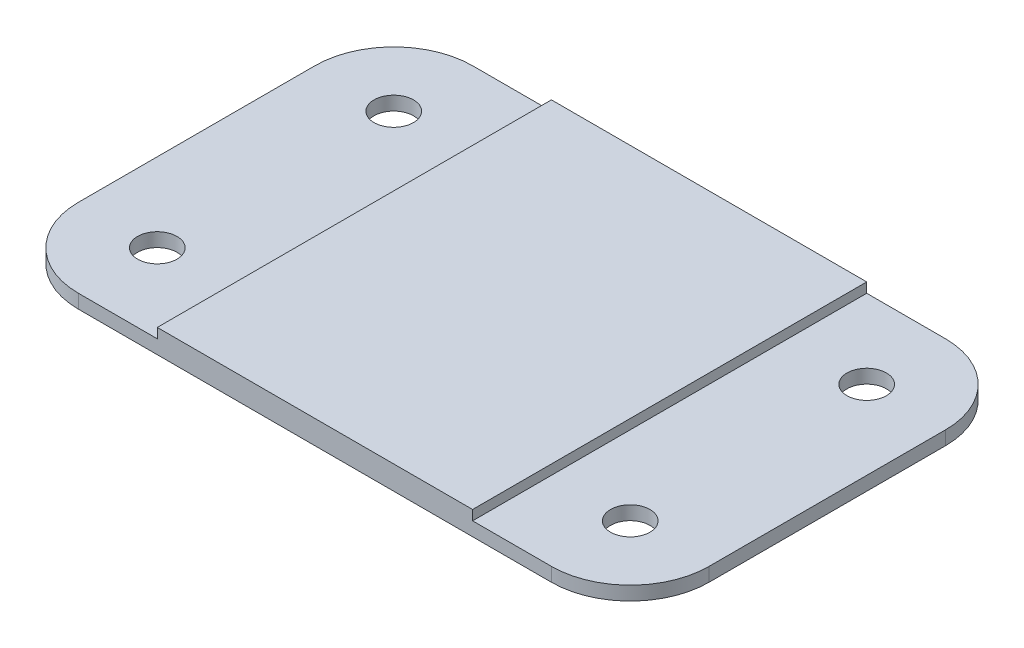
SolidWorks part; units mm, degrees
ref_plane "Front Plane" through (0, 0, 0) normal (0, 0, 1) x (1, 0, 0)
ref_plane "Top Plane" through (0, 0, 0) normal (0, 1, 0) x (1, 0, 0)
ref_plane "Right Plane" through (0, 0, 0) normal (1, 0, 0) x (0, 0, -1)
sketch "Sketch1" plane through (0, 0, 0) normal (0, 1, 0) x (1, 0, 0)
  line L1 (-76.2, 63.5) -> (76.2, 63.5)
  line L2 (-101.6, 38.1) -> (-101.6, -38.1)
  line L3 (-76.2, -63.5) -> (76.2, -63.5)
  line L4 (101.6, 38.1) -> (101.6, -38.1)
  line L5 (-101.6, 63.5) -> (101.6, -63.5) construction
  line L6 (-101.6, -63.5) -> (101.6, 63.5) construction
  arc A0 (76.2, 63.5) -> (101.6, 38.1) centre (76.2, 38.1) cw
  arc A1 (-101.6, -38.1) -> (-76.2, -63.5) centre (-76.2, -38.1) ccw
  arc A2 (-76.2, 63.5) -> (-101.6, 38.1) centre (-76.2, 38.1) ccw
  arc A3 (76.2, -63.5) -> (101.6, -38.1) centre (76.2, -38.1) ccw
  circle A4 centre (-76.2, 38.1) radius 6.35
  circle A6 centre (76.2, -38.1) radius 6.35
  circle A7 centre (76.2, 38.1) radius 6.35
  circle A9 centre (-76.2, -38.1) radius 6.35
  point P0 (0, 0)
  dimension "D3" = 25.4
  dimension "D4" = 12.7
  dimension "D5" = 12.7
  dimension "D6" = 12.7
  dimension "D7" = 12.7
  dimension "D1" = 127
  dimension "D2" = 203.2
extrude "Boss-Extrude2" add sketch "Sketch1" along normal blind 7.62 contours A3 L3 A1 L2 A2 L1 A0 L4 | A4 | A9 | A6 | A7
sketch "Sketch3" plane through (0, 7.62, 0) normal (0, 1, 0) x (1, 0, 0)
  line L0 (-50.8, 63.5) -> (-50.8, -63.5)
  line L1 (50.8, 63.5) -> (50.8, -63.5)
  line L4 (101.6, -38.1) -> (101.6, 38.1)
  line L5 (76.2, 63.5) -> (-76.2, 63.5)
  line L6 (-101.6, 38.1) -> (-101.6, -38.1)
  line L7 (-76.2, -63.5) -> (76.2, -63.5)
  line L8 (101.6, -38.1) -> (101.6, 38.1)
  line L9 (76.2, 63.5) -> (-76.2, 63.5)
  line L10 (-101.6, 38.1) -> (-101.6, -38.1)
  line L11 (-76.2, -63.5) -> (76.2, -63.5)
  arc A4 (101.6, 38.1) -> (76.2, 63.5) centre (76.2, 38.1) ccw
  arc A5 (-76.2, 63.5) -> (-101.6, 38.1) centre (-76.2, 38.1) ccw
  arc A6 (-101.6, -38.1) -> (-76.2, -63.5) centre (-76.2, -38.1) ccw
  arc A7 (76.2, -63.5) -> (101.6, -38.1) centre (76.2, -38.1) ccw
  arc A8 (101.6, 38.1) -> (76.2, 63.5) centre (76.2, 38.1) ccw
  arc A9 (-76.2, 63.5) -> (-101.6, 38.1) centre (-76.2, 38.1) ccw
  arc A10 (-101.6, -38.1) -> (-76.2, -63.5) centre (-76.2, -38.1) ccw
  arc A11 (76.2, -63.5) -> (101.6, -38.1) centre (76.2, -38.1) ccw
  circle M11 centre (76.2, -38.1) radius 6.35
  circle M12 centre (-76.2, 38.1) radius 6.35
  line M13 (101.6, -38.1) -> (101.6, 38.1)
  arc M14 (101.6, 38.1) -> (76.2, 63.5) centre (76.2, 38.1) ccw
  line M15 (76.2, 63.5) -> (-76.2, 63.5)
  arc M16 (-76.2, 63.5) -> (-101.6, 38.1) centre (-76.2, 38.1) ccw
  line M17 (-101.6, 38.1) -> (-101.6, -38.1)
  arc M18 (-101.6, -38.1) -> (-76.2, -63.5) centre (-76.2, -38.1) ccw
  line M19 (-76.2, -63.5) -> (76.2, -63.5)
  arc M20 (76.2, -63.5) -> (101.6, -38.1) centre (76.2, -38.1) ccw
  circle M21 centre (-76.2, -38.1) radius 6.35
  circle M22 centre (76.2, 38.1) radius 6.35
  dimension "D2" = 50.8
  dimension "D3" = 50.8
  dimension "D1" = 0
extrude "Cut-Extrude2" cut sketch "Sketch3" against normal blind 3.175 contours L0 M15 M16 M17 M18 M19 M12 M21 | L1 M15 M19 M20 M13 M14 M11 M22
sketch "Sketch4" plane through (0, 0, 0) normal (0, -1, 0) x (1, 0, 0)
  line L1 (-12.7, 12.7) -> (12.7, 12.7)
  line L2 (-12.7, 12.7) -> (-12.7, -12.7)
  line L3 (-12.7, -12.7) -> (12.7, -12.7)
  line L4 (12.7, 12.7) -> (12.7, -12.7)
  line L5 (-12.7, 12.7) -> (12.7, -12.7) construction
  line L6 (-12.7, -12.7) -> (12.7, 12.7) construction
  point P0 (0, 0)
  dimension "D1" = 25.4
  dimension "D2" = 25.4
extrude "Boss-Extrude3" add sketch "Sketch4" along normal blind 50.8 contours L2 L1 L4 L3
